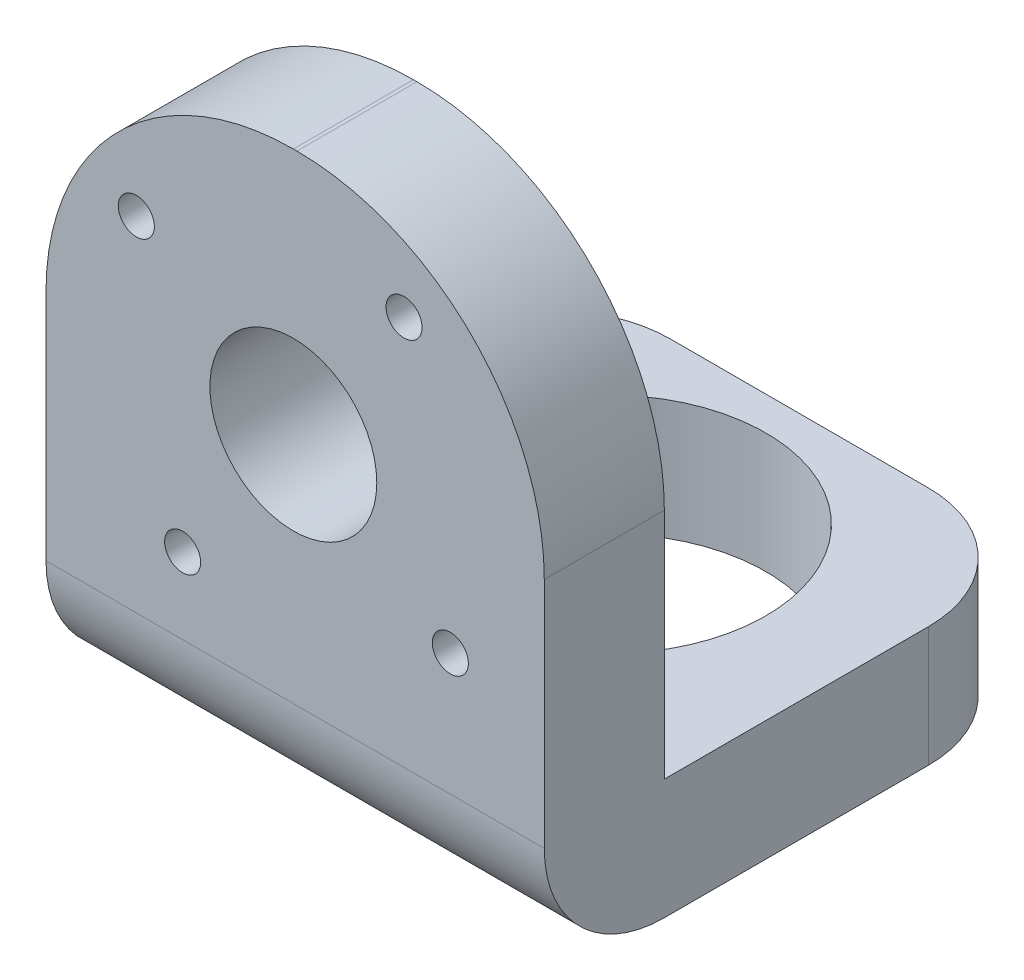
SolidWorks part; units mm, degrees
ref_plane "Front Plane" through (0, 0, 0) normal (0, 0, 1) x (1, 0, 0)
ref_plane "Top Plane" through (0, 0, 0) normal (0, 1, 0) x (1, 0, 0)
ref_plane "Right Plane" through (0, 0, 0) normal (1, 0, 0) x (0, 0, -1)
sketch "Sketch1" plane through (0, 0, 0) normal (0, 0, 1) x (1, 0, 0)
  line L1 (-0.075, 12.5) -> (0.075, 12.5)
  line L2 (-10.375, 2.2) -> (-10.375, -12.5)
  line L3 (-10.375, -12.5) -> (10.375, -12.5)
  line L4 (10.375, 2.2) -> (10.375, -12.5)
  line L5 (-10.375, 12.5) -> (10.375, -12.5) construction
  line L6 (-10.375, -12.5) -> (10.375, 12.5) construction
  arc A0 (-0.075, 12.5) -> (-10.375, 2.2) centre (-0.075, 2.2) ccw
  arc A1 (0.075, 12.5) -> (10.375, 2.2) centre (0.075, 2.2) cw
  point P0 (0, 0)
  dimension "D3" = 10.3
  dimension "D1" = 20.75
  dimension "D2" = 25
extrude "Boss-Extrude1" add sketch "Sketch1" along normal blind 5
sketch "Sketch2" plane through (0, 0, 5) normal (0, 0, 1) x (1, 0, 0)
  line L0 (10.375, -12.5) -> (10.375, 2.2) construction
  line L1 (-10.375, -12.5) -> (10.375, -12.5)
  line L2 (-10.375, -12.5) -> (-10.375, -7.5)
  line L3 (-10.375, -7.5) -> (10.375, -7.5)
  line L4 (10.375, -12.5) -> (10.375, -7.5)
  dimension "D1" = 5
extrude "Boss-Extrude2" add sketch "Sketch2" against normal blind 16 from surface at -5 starting at face at (0, 1.4444, 0)
sketch "Sketch3" plane through (0, -7.5, 0) normal (0, 1, 0) x (1, 0, 0)
  line L1 (10.375, 16) -> (-10.375, 16) construction
  line L2 (10.375, 0) -> (-10.375, 0) construction
  circle A0 centre (0, 8) radius 6.6
  point P7 (0, 16)
  dimension "D1" = 13.2
  dimension "D2" = 8
extrude "Cut-Extrude1" cut sketch "Sketch3" against normal through all
fillet "Fillet2" radius 5 2 edges at (10.375, -10, -16) (-10.375, -10, -16)
fillet "Fillet3" radius 5 1 edges at (0, -12.5, 5)
sketch "Sketch5" plane through (0, 0, 5) normal (0, 0, 1) x (1, 0, 0)
  circle A0 centre (-0.075, 2.2) radius 3.475
  circle A1 centre (-6.6131, 6.8101) radius 0.75
  circle A2 centre (4.5351, 8.7381) radius 0.75
  circle A3 centre (-4.6851, -4.3381) radius 0.75
  circle A4 centre (6.4631, -2.4101) radius 0.75
extrude "Cut-Extrude3" cut sketch "Sketch5" against normal through all
